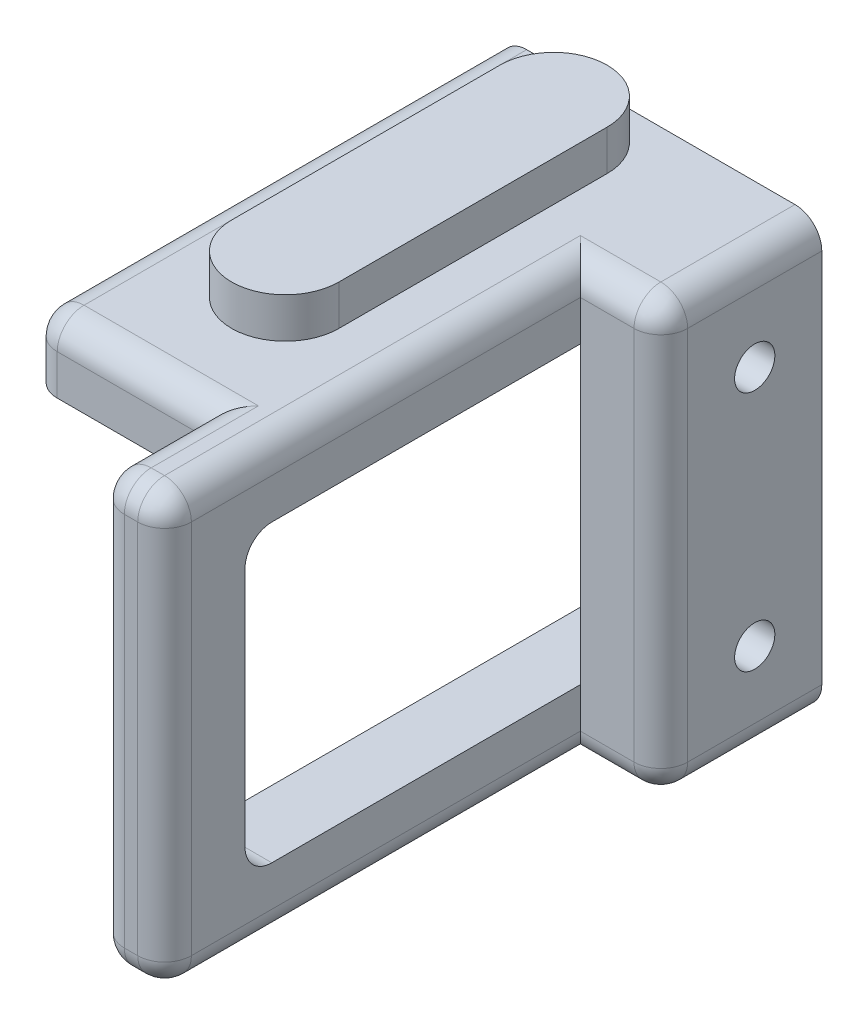
SolidWorks part; units mm, degrees
ref_plane "Front Plane" through (0, 0, 0) normal (0, 0, 1) x (1, 0, 0)
ref_plane "Top Plane" through (0, 0, 0) normal (0, 1, 0) x (1, 0, 0)
ref_plane "Right Plane" through (0, 0, 0) normal (1, 0, 0) x (0, 0, -1)
sketch "U" plane through (0, 0, 0) normal (1, 0, 0) x (0, 0, -1)
  line L0 (0, 22) -> (0, 27)
  line L1 (0, 0) -> (-35, 0)
  line L3 (0, 22) -> (-35, 22)
  line L4 (-37, 2) -> (-37, 20)
  line L5 (0, 27) -> (-41, 27)
  line L6 (-43, 25) -> (-43, -3)
  line L7 (-41, -5) -> (0, -5)
  line L8 (0, -5) -> (0, 0)
  arc A0 (-41, -5) -> (-43, -3) centre (-41, -3) cw
  arc A1 (-41, 27) -> (-43, 25) centre (-41, 25) ccw
  arc A2 (-37, 2) -> (-35, 0) centre (-35, 2) ccw
  arc A3 (-37, 20) -> (-35, 22) centre (-35, 20) cw
  point P15 (-37, 0)
  point P18 (-37, 22)
  dimension "D5" = 2
  dimension "D6" = 2
  dimension "D1" = 37
  dimension "D2" = 22
  dimension "D3" = 5
  dimension "D4" = 6
extrude "Boss-Extrude1" add sketch "U" against normal blind 5
sketch "Sketch2" plane through (0, 0, 0) normal (1, 0, 0) x (0, 0, -1)
  line L0 (0, 27) -> (-41, 27) construction
  line L1 (0, -5) -> (-12, -5)
  line L2 (0, -5) -> (0, 27)
  line L3 (0, 27) -> (-12, 27)
  line L4 (-12, -5) -> (-12, 27)
  dimension "D1" = 12
extrude "Boss-Extrude2" add sketch "Sketch2" along normal blind 6
sketch "AgujerosMotor" plane through (6, 0, 0) normal (1, 0, 0) x (0, 0, -1)
  line L0 (-5, 22) -> (-5, 0) construction
  line L1 (-12, 22) -> (0, 22) construction
  line L2 (-12, 22) -> (-12, 0) construction
  line L3 (-12, 0) -> (0, 0) construction
  line L4 (0, 22) -> (0, 0) construction
  line L5 (-5, 11) -> (0, 11) construction
  circle A0 centre (-5, 2) radius 1.5
  circle A1 centre (-5, 20) radius 1.5
  dimension "D2" = 3
  dimension "D1" = 5
  dimension "D3" = 2
extrude "Cut-Extrude1" cut sketch "AgujerosMotor" against normal up to next
fillet "Fillet1" radius 2 2 edges at (6, 27, 6) (6, -5, 6)
sketch "Sketch5" plane through (-5, 0, 0) normal (-1, 0, 0) x (0, 0, 1)
  line L0 (35, 22) -> (0, 22) construction
  line L5 (0, 27) -> (35, 27)
  line L6 (0, 27) -> (0, 22)
  line L7 (0, 22) -> (35, 22)
  line L8 (35, 27) -> (35, 22)
  arc A0 (37, 20) -> (35, 22) centre (35, 20) ccw construction
extrude "Boss-Extrude3" add sketch "Sketch5" along normal blind 13
fillet "Fillet2" radius 2 1 edges at (-18, 24.5, 35)
fillet "Fillet3" radius 2 15 edges at (-5, 27, 38) (-5, 26.4142, 42.4142) (-5, 11, 43) (-5, -5, 20.5) (0, 27, 26.5) (0, 26.4142, 42.4142) (0, 11, 43) (0, -5, 26.5) (2, 27, 12) (5.4142, 26.4142, 12) (2, -5, 12) (5.4142, -4.4142, 12) (-5, -4.4142, 42.4142) (0, -4.4142, 42.4142) (6, 11, 12)
fillet "Fillet4" radius 2 3 edges at (-18, 27, 16.5) (-17.4142, 27, 34.4142) (-9.5, 27, 35)
sketch "Encastre" plane through (0, 27, 0) normal (0, 1, 0) x (1, 0, 0)
  line L0 (-9, -5) -> (-9, -25) construction
  line L1 (-5, -5) -> (-5, -25)
  line L2 (-13, -5) -> (-13, -25)
  line L3 (-16, 0) -> (4, 0) construction
  line L4 (-2, -41) -> (-2, -10) construction
  arc A0 (-5, -5) -> (-13, -5) centre (-9, -5) ccw
  arc A1 (-13, -25) -> (-5, -25) centre (-9, -25) ccw
  point P2 (-9, -15)
  dimension "D5" = 4
  dimension "D1" = 20
  dimension "D2" = 8
  dimension "D3" = 5
  dimension "D4" = 3
extrude "Boss-Extrude4" add sketch "Encastre" along normal blind 3
